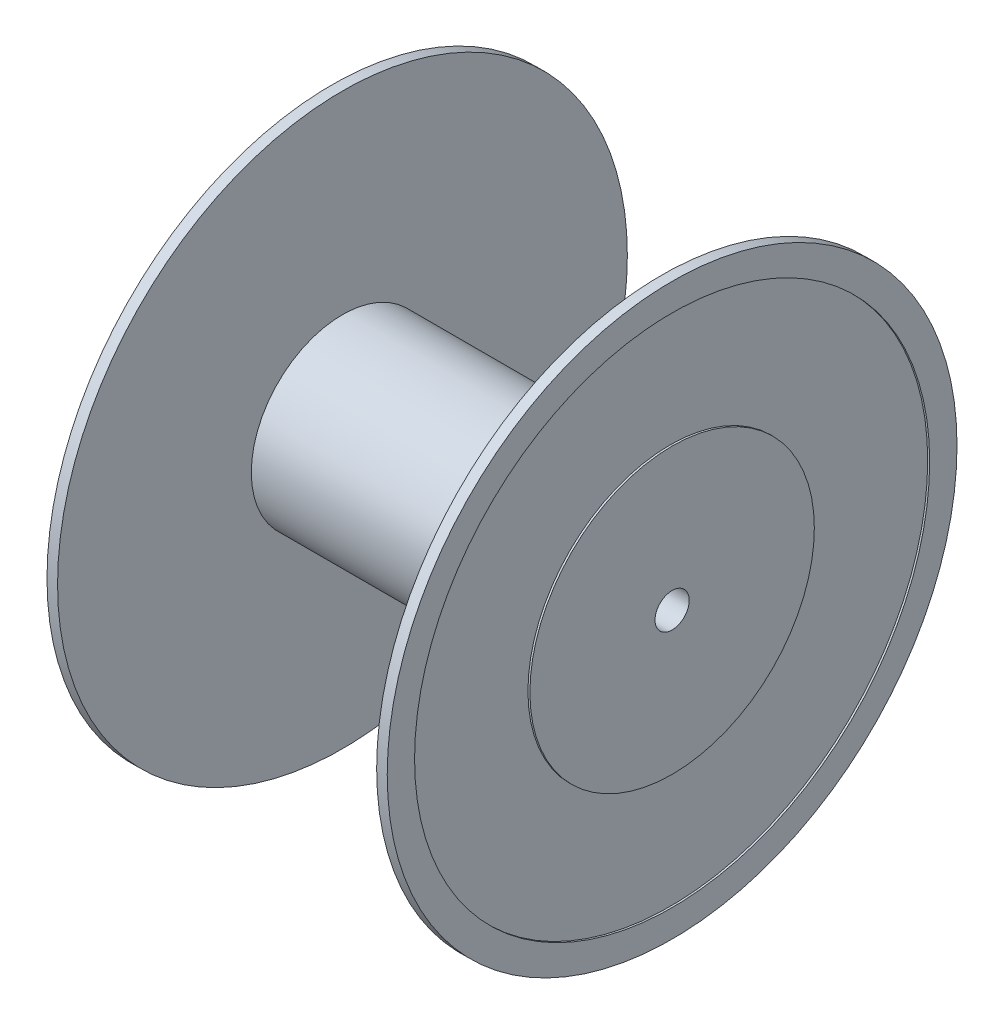
SolidWorks part; units mm, degrees
ref_plane "Front Plane" through (0, 0, 0) normal (0, 0, 1) x (1, 0, 0)
ref_plane "Top Plane" through (0, 0, 0) normal (0, 1, 0) x (1, 0, 0)
ref_plane "Right Plane" through (0, 0, 0) normal (1, 0, 0) x (0, 0, -1)
sketch "Sketch1" plane through (0, 0, 0) normal (1, 0, 0) x (0, 0, -1)
  circle A0 centre (0, 0) radius 25.4
  dimension "D1" = 50.8
extrude "Boss-Extrude1" add sketch "Sketch1" along normal blind 44.45
sketch "Sketch2" plane through (44.45, 0, 0) normal (1, 0, 0) x (0, 0, -1)
  circle A0 centre (0, 0) radius 79.375
  dimension "D1" = 158.75
extrude "Boss-Extrude2" add sketch "Sketch2" along normal blind 2.4003
sketch "Sketch3" plane through (46.8503, 0, 0) normal (1, 0, 0) x (0, 0, -1)
  circle A0 centre (0, 0) radius 79.375
  circle A1 centre (0, 0) radius 79.375 construction
  circle A2 centre (0, 0) radius 71.755
  dimension "D1" = 7.62
extrude "Boss-Extrude3" add sketch "Sketch3" along normal blind 0.5461
sketch "Sketch4" plane through (46.8503, 0, 0) normal (1, 0, 0) x (0, 0, -1)
  circle A0 centre (0, 0) radius 39.624
  dimension "D1" = 79.248
extrude "Boss-Extrude4" add sketch "Sketch4" along normal blind 0.5461
sketch "Sketch5" plane through (47.3964, 0, 0) normal (1, 0, 0) x (0, 0, -1)
  circle A0 centre (0, 0) radius 4.7625
  dimension "D1" = 9.525
extrude "Cut-Extrude1" cut sketch "Sketch5" against normal through all
mirror "Mirror1" about plane through (0, 0, 0) normal (1, 0, 0) of "Cut-Extrude1", "Boss-Extrude3", "Boss-Extrude4", "Boss-Extrude2", "Boss-Extrude1"
